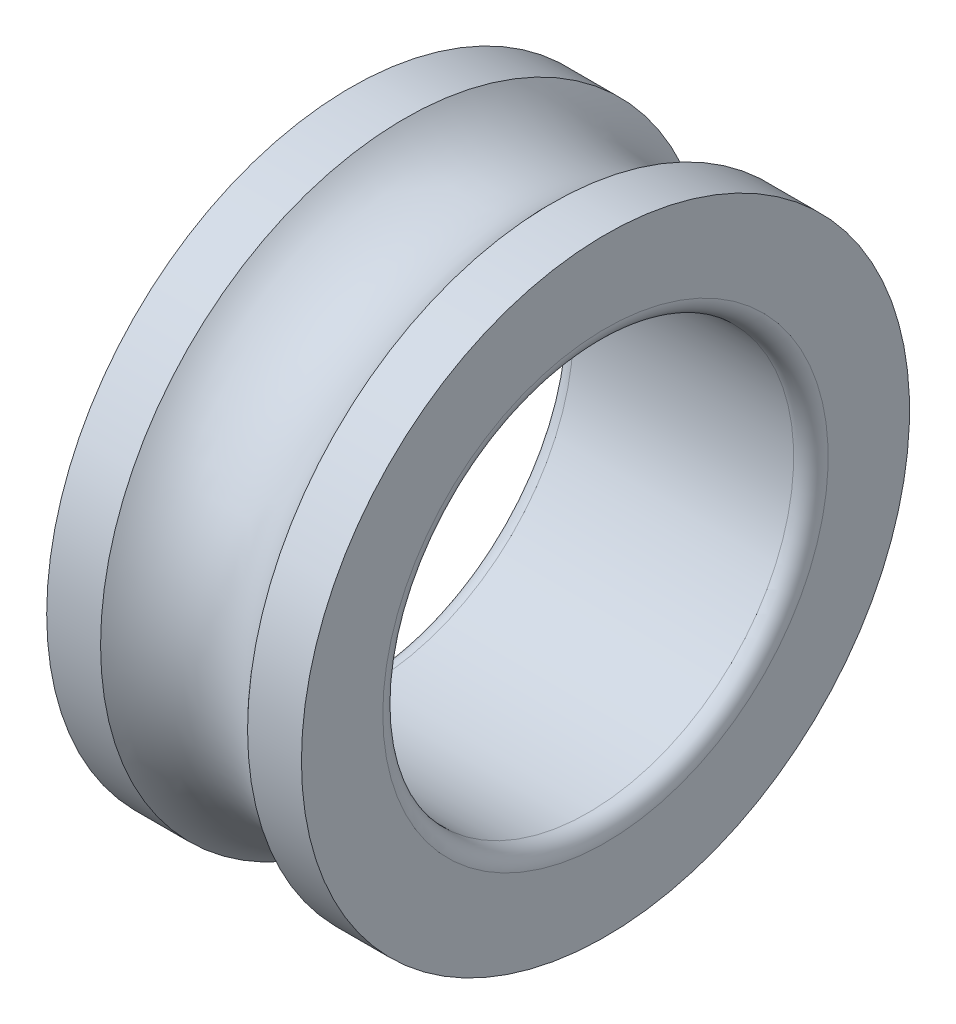
SolidWorks part; units mm, degrees
ref_plane "Front Plane" through (0, 0, 0) normal (0, 0, 1) x (1, 0, 0)
ref_plane "Top Plane" through (0, 0, 0) normal (0, 1, 0) x (1, 0, 0)
ref_plane "Right Plane" through (0, 0, 0) normal (1, 0, 0) x (0, 0, -1)
sketch "Sketch1" plane through (0, 0, 0) normal (0, 0, 1) x (1, 0, 0)
  line L0 (-9.8694, 0) -> (20.4347, 0) construction
  line L1 (0, 25) -> (0, 0) construction
  line L2 (13.4, 25) -> (-13.4, 25)
  line L3 (15.5, 27.1) -> (15.5, 37)
  line L4 (15.5, 37) -> (8.9443, 37)
  line L5 (-15.5, 27.1) -> (-15.5, 37)
  line L6 (15.5, 25) -> (-15.5, 37) construction
  line L7 (15.5, 37) -> (-15.5, 25) construction
  line L8 (-8.9443, 37) -> (-15.5, 37)
  arc A0 (-8.9443, 37) -> (8.9443, 37) centre (0, 45) ccw
  arc A1 (13.4, 25) -> (15.5, 27.1) centre (13.4, 27.1) ccw
  arc A2 (-13.4, 25) -> (-15.5, 27.1) centre (-13.4, 27.1) cw
  point P3 (0, 31)
  dimension "D5" = 12
  dimension "D7" = 2.1
  dimension "D1" = 31
  dimension "D2" = 25
  dimension "D3" = 37
  dimension "D4" = 8
  dimension "D6" = 6.5557
revolve "Revolve1" add sketch "Sketch1" angle 360 about L0
